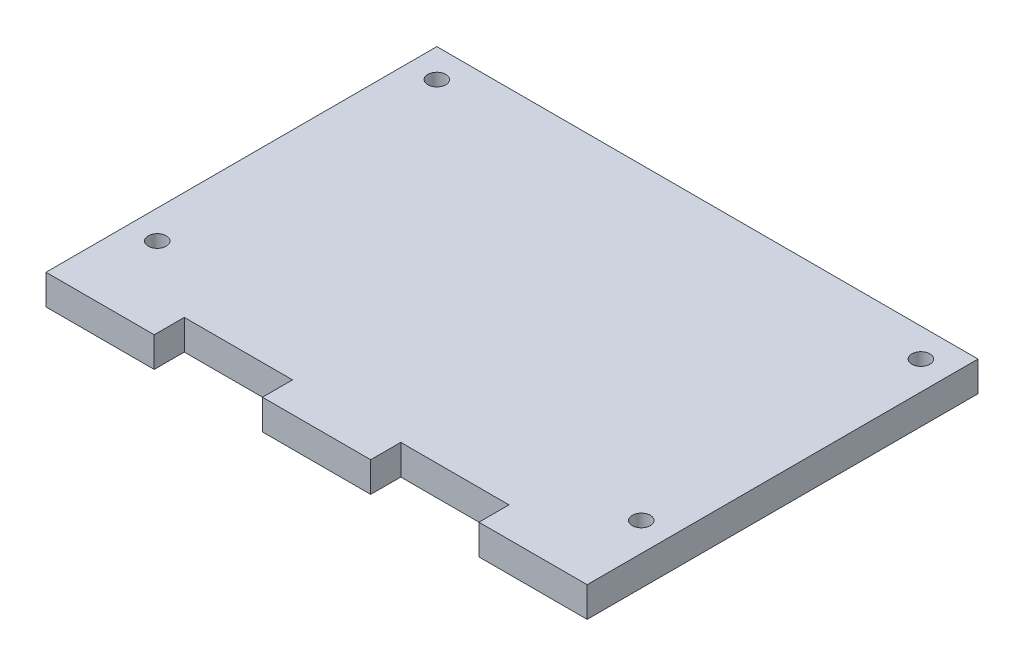
SolidWorks part; units mm, degrees
ref_plane "Front Plane" through (0, 0, 0) normal (0, 0, 1) x (1, 0, 0)
ref_plane "Top Plane" through (0, 0, 0) normal (0, 1, 0) x (1, 0, 0)
ref_plane "Right Plane" through (0, 0, 0) normal (1, 0, 0) x (0, 0, -1)
sketch "Sketch1" plane through (0, 0, 0) normal (0, 1, 0) x (1, 0, 0)
  line L0 (54, 0) -> (72, 0)
  line L1 (18, 0) -> (36, 0)
  line L2 (0, 0) -> (0, 60)
  line L3 (0, 60) -> (90, 60)
  line L4 (90, 0) -> (90, 60)
  line L6 (0, 0) -> (0, -5)
  line L7 (0, -5) -> (18, -5)
  line L8 (18, 0) -> (18, -5)
  line L10 (36, 0) -> (36, -5)
  line L11 (36, -5) -> (54, -5)
  line L12 (54, 0) -> (54, -5)
  line L14 (72, 0) -> (72, -5)
  line L15 (72, -5) -> (90, -5)
  line L16 (90, 0) -> (90, -5)
  point P15 (72, -2.5)
  dimension "D1" = 60
  dimension "D2" = 90
  dimension "D3" = 18
  dimension "D4" = 18
  dimension "D5" = 18
  dimension "D6" = 18
  dimension "D7" = 5
extrude "Boss-Extrude1" add sketch "Sketch1" along normal blind 5
sketch "Sketch2" plane through (0, 5, 0) normal (0, 1, 0) x (1, 0, 0)
  line L0 (90, -5) -> (90, 60) construction
  line L1 (90, 60) -> (0, 60) construction
  circle A0 centre (4.75, 55.25) radius 1.5
  circle A1 centre (85.25, 55.25) radius 1.5
  circle A2 centre (85.25, 8.75) radius 1.5
  circle A3 centre (4.75, 8.75) radius 1.5
  dimension "D1" = 3
  dimension "D2" = 46.5
  dimension "D3" = 46.5
  dimension "D4" = 80.5
  dimension "D5" = 4.75
  dimension "D6" = 4.75
  dimension "D7" = 80.5
extrude "Cut-Extrude1" cut sketch "Sketch2" against normal blind 5
